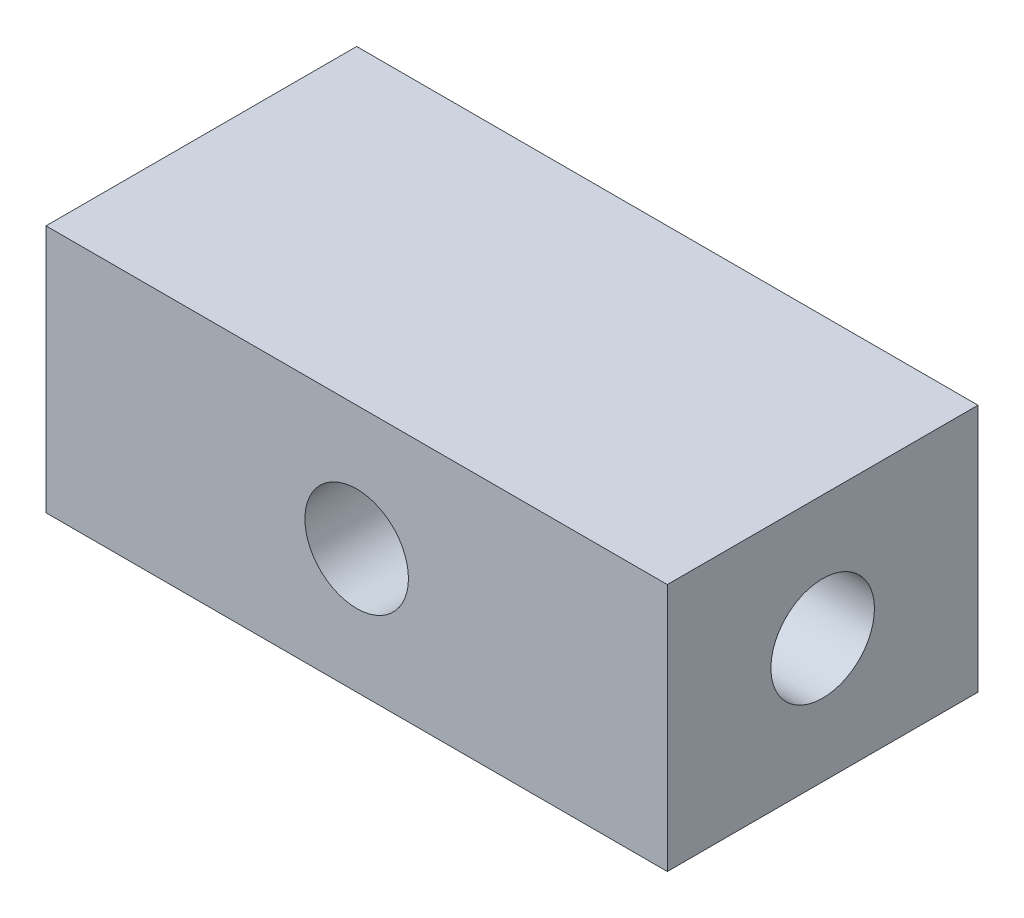
SolidWorks part; units mm, degrees
material "Lega 1060"
ref_plane "Piano frontale" through (0, 0, 0) normal (0, 0, 1) x (1, 0, 0)
ref_plane "Piano superiore" through (0, 0, 0) normal (0, 1, 0) x (1, 0, 0)
ref_plane "Piano destro" through (0, 0, 0) normal (1, 0, 0) x (0, 0, -1)
sketch "Schizzo1" plane through (0, 0, 0) normal (0, 0, 1) x (1, 0, 0)
  line L1 (15, -6) -> (-15, -6)
  line L2 (15, -6) -> (15, 6)
  line L3 (15, 6) -> (-15, 6)
  line L4 (-15, -6) -> (-15, 6)
  line L5 (15, -6) -> (-15, 6) construction
  line L6 (15, 6) -> (-15, -6) construction
  circle A0 centre (0, 0) radius 2.5
  point P0 (0, 0)
  dimension "D3" = 5
  dimension "D1" = 30
  dimension "D2" = 12
extrude "Estrusione-Estrusione1" add sketch "Schizzo1" along normal mid plane 15
sketch "Schizzo3" plane through (15, 0, 0) normal (1, 0, 0) x (0, 0, -1)
  circle A0 centre (0, 0) radius 2.5
  dimension "D1" = 5
extrude "Taglio-Estrusione1" cut sketch "Schizzo3" against normal up to surface (30 mm away) up to face at (-15, 0, 0)
